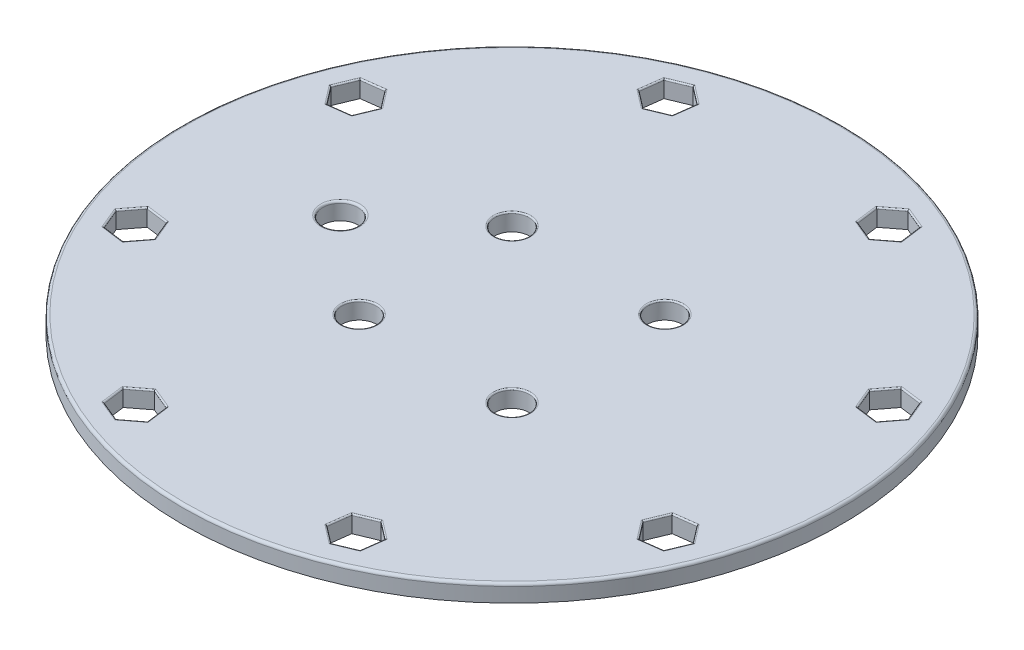
SolidWorks part; units mm, degrees
ref_plane "前视基准面" through (0, 0, 0) normal (0, 0, 1) x (1, 0, 0)
ref_plane "上视基准面" through (0, 0, 0) normal (0, 1, 0) x (1, 0, 0)
ref_plane "右视基准面" through (0, 0, 0) normal (1, 0, 0) x (0, 0, -1)
other "Configuration Table"
sketch "草图1" plane through (0, 0, 0) normal (0, 0, 1) x (1, 0, 0)
  line L0 (48, 6) -> (0, 6)
  line L1 (0, 6) -> (0, 0)
  line L2 (0, 0) -> (48, 0)
  line L3 (48, 0) -> (48, 6)
  line L4 (0, 6) -> (0, 0) construction
revolve "旋转1" add sketch "草图1" angle 360 about L4
sketch "草图2" plane through (0, 6, 0) normal (0, 1, 0) x (-1, 0, 0)
  line L0 (42.0084, 15.6507) -> (40.7712, 18.6377)
  line L1 (40.7712, 18.6377) -> (37.5657, 19.0598)
  line L2 (37.5657, 19.0598) -> (35.5974, 16.4947)
  line L3 (35.5974, 16.4947) -> (36.8347, 13.5077)
  line L4 (36.8347, 13.5077) -> (40.0402, 13.0857)
  line L5 (40.0402, 13.0857) -> (42.0084, 15.6507)
extrude "切除-拉伸1" cut sketch "草图2" against normal blind 2.5
sketch "草图3" plane through (0, 6, 0) normal (0, 1, 0) x (-1, 0, 0)
  line L0 (18.6377, 40.7712) -> (15.6507, 42.0084)
  line L1 (15.6507, 42.0084) -> (13.0857, 40.0402)
  line L2 (13.0857, 40.0402) -> (13.5077, 36.8347)
  line L3 (13.5077, 36.8347) -> (16.4947, 35.5974)
  line L4 (16.4947, 35.5974) -> (19.0598, 37.5657)
  line L5 (19.0598, 37.5657) -> (18.6377, 40.7712)
extrude "切除-拉伸2" cut sketch "草图3" against normal blind 2.5
sketch "草图4" plane through (0, 6, 0) normal (0, 1, 0) x (-1, 0, 0)
  line L0 (-15.6507, 42.0084) -> (-18.6377, 40.7712)
  line L1 (-18.6377, 40.7712) -> (-19.0598, 37.5657)
  line L2 (-19.0598, 37.5657) -> (-16.4947, 35.5974)
  line L3 (-16.4947, 35.5974) -> (-13.5077, 36.8347)
  line L4 (-13.5077, 36.8347) -> (-13.0857, 40.0402)
  line L5 (-13.0857, 40.0402) -> (-15.6507, 42.0084)
extrude "切除-拉伸3" cut sketch "草图4" against normal blind 2.5
sketch "草图5" plane through (0, 6, 0) normal (0, 1, 0) x (-1, 0, 0)
  line L0 (-40.7712, 18.6377) -> (-42.0084, 15.6507)
  line L1 (-42.0084, 15.6507) -> (-40.0402, 13.0857)
  line L2 (-40.0402, 13.0857) -> (-36.8347, 13.5077)
  line L3 (-36.8347, 13.5077) -> (-35.5974, 16.4947)
  line L4 (-35.5974, 16.4947) -> (-37.5657, 19.0598)
  line L5 (-37.5657, 19.0598) -> (-40.7712, 18.6377)
extrude "切除-拉伸4" cut sketch "草图5" against normal blind 2.5
sketch "草图6" plane through (0, 6, 0) normal (0, 1, 0) x (-1, 0, 0)
  line L0 (-42.0084, -15.6507) -> (-40.7712, -18.6377)
  line L1 (-40.7712, -18.6377) -> (-37.5657, -19.0598)
  line L2 (-37.5657, -19.0598) -> (-35.5974, -16.4947)
  line L3 (-35.5974, -16.4947) -> (-36.8347, -13.5077)
  line L4 (-36.8347, -13.5077) -> (-40.0402, -13.0857)
  line L5 (-40.0402, -13.0857) -> (-42.0084, -15.6507)
extrude "切除-拉伸5" cut sketch "草图6" against normal blind 2.5
sketch "草图7" plane through (0, 6, 0) normal (0, 1, 0) x (-1, 0, 0)
  line L0 (-18.6377, -40.7712) -> (-15.6507, -42.0084)
  line L1 (-15.6507, -42.0084) -> (-13.0857, -40.0402)
  line L2 (-13.0857, -40.0402) -> (-13.5077, -36.8347)
  line L3 (-13.5077, -36.8347) -> (-16.4947, -35.5974)
  line L4 (-16.4947, -35.5974) -> (-19.0598, -37.5657)
  line L5 (-19.0598, -37.5657) -> (-18.6377, -40.7712)
extrude "切除-拉伸6" cut sketch "草图7" against normal blind 2.5
sketch "草图8" plane through (0, 6, 0) normal (0, 1, 0) x (-1, 0, 0)
  line L0 (15.6507, -42.0084) -> (18.6377, -40.7712)
  line L1 (18.6377, -40.7712) -> (19.0598, -37.5657)
  line L2 (19.0598, -37.5657) -> (16.4947, -35.5974)
  line L3 (16.4947, -35.5974) -> (13.5077, -36.8347)
  line L4 (13.5077, -36.8347) -> (13.0857, -40.0402)
  line L5 (13.0857, -40.0402) -> (15.6507, -42.0084)
extrude "切除-拉伸7" cut sketch "草图8" against normal blind 2.5
sketch "草图9" plane through (0, 6, 0) normal (0, 1, 0) x (-1, 0, 0)
  line L0 (40.7712, -18.6377) -> (42.0084, -15.6507)
  line L1 (42.0084, -15.6507) -> (40.0402, -13.0857)
  line L2 (40.0402, -13.0857) -> (36.8347, -13.5077)
  line L3 (36.8347, -13.5077) -> (35.5974, -16.4947)
  line L4 (35.5974, -16.4947) -> (37.5657, -19.0598)
  line L5 (37.5657, -19.0598) -> (40.7712, -18.6377)
extrude "切除-拉伸8" cut sketch "草图9" against normal blind 2.5
hole_wizard "Ø5.0 (5) 直径孔1" positions "草图11" profile "草图10" hole size "Ø5.0" standard "ANSI Metric"
sketch "草图11" plane through (0, 6, 0) normal (0, 1, 0) x (1, 0, 0)
  point P0 (11.1369, 11.1369)
  point P1 (11.1369, -11.1369)
  point P2 (-11.1369, -11.1369)
  point P3 (-11.1369, 11.1369)
sketch "草图10" plane through (11.1369, 6, -11.1369) normal (1, 0, 0) x (0, 0, 1)
  line L0 (0, 0) -> (0, 6)
  line L1 (0, 6) -> (2.5, 6)
  line L2 (2.5, 6) -> (2.5, 0)
  line L5 (2.5, 0) -> (0, 0)
  line L11 (0, -6.35) -> (0, 107.95) construction
  dimension "通孔孔直径" = 5
  dimension "通孔孔深度" = 6
hole_wizard "Ø3.0 (3) 直径孔1" positions "草图13" profile "草图12" hole size "Ø3.0" standard "ANSI Metric"
sketch "草图13" plane through (0, 3.5, 0) normal (0, 1, 0) x (1, 0, 0)
  point P0 (-38.8029, -16.0727)
  point P1 (-16.0727, -38.8029)
  point P2 (16.0727, -38.8029)
  point P3 (38.8029, -16.0727)
  point P4 (38.8029, 16.0727)
  point P5 (16.0727, 38.8029)
  point P6 (-16.0727, 38.8029)
  point P7 (-38.8029, 16.0727)
sketch "草图12" plane through (-38.8029, 3.5, 16.0727) normal (1, 0, 0) x (0, 0, 1)
  line L0 (0, 0) -> (0, 3.5)
  line L1 (0, 3.5) -> (1.5, 3.5)
  line L2 (1.5, 3.5) -> (1.5, 0)
  line L5 (1.5, 0) -> (0, 0)
  line L11 (0, -6.35) -> (0, 107.95) construction
  dimension "通孔孔直径" = 3
  dimension "通孔孔深度" = 3.5
hole_wizard "Ø5.1 (5.1) 直径孔1" positions "草图15" profile "草图14" hole size "Ø5.1" standard "ANSI Metric"
sketch "草图15" plane through (0, 6, 0) normal (0, 1, 0) x (1, 0, 0)
  point P0 (-25, 0)
sketch "草图14" plane through (-25, 6, 0) normal (1, 0, 0) x (0, 0, 1)
  line L0 (0, 0) -> (0, 3.5)
  line L1 (0, 3.5) -> (2.55, 3.5)
  line L2 (2.55, 3.5) -> (2.55, 0)
  line L5 (2.55, 0) -> (0, 0)
  line L10 (0, 3.5) -> (-2.55, 3.5) construction
  line L11 (0, -6.35) -> (0, 107.95) construction
  dimension "孔直径" = 5.1
  dimension "孔深度" = 3.5
  dimension "导头角度" = 180
fillet "圆角1" radius 0.2 60 edges at (-41.3898, 6, -17.1442) (-41.0243, 6, -14.3682) (-39.1684, 6, -18.8487) (-38.4375, 6, -13.2967) (-36.5816, 6, -17.7772) (-36.2161, 6, -15.0012) (18.8487, 6, -39.1684) (17.1442, 6, -41.3898) (17.7772, 6, -36.5816) (14.3682, 6, -41.0243) (15.0012, 6, -36.2161) (13.2967, 6, -38.4375) (-36.5816, 6, 17.7772) (-39.1684, 6, 18.8487) (-36.2161, 6, 15.0012) (-41.3898, 6, 17.1442) (-38.4375, 6, 13.2967) (-41.0243, 6, 14.3682) (-16.0727, 3.5, -37.3029) (-17.1442, 6, -41.3898) (-18.8487, 6, -39.1684) (-14.3682, 6, -41.0243) (-17.7772, 6, -36.5816) (-13.2967, 6, -38.4375) (-15.0012, 6, -36.2161) (-38.8029, 3.5, 17.5727) (41.3898, 6, -17.1442) (39.1684, 6, -18.8487) (41.0243, 6, -14.3682) (36.5816, 6, -17.7772) (38.4375, 6, -13.2967) (36.2161, 6, -15.0012) (-13.2967, 6, 38.4375) (-14.3682, 6, 41.0243) (-15.0012, 6, 36.2161) (-17.1442, 6, 41.3898) (-17.7772, 6, 36.5816) (-18.8487, 6, 39.1684) (16.0727, 3.5, 40.3029) (17.7772, 6, 36.5816) (18.8487, 6, 39.1684) (15.0012, 6, 36.2161) (17.1442, 6, 41.3898) (13.2967, 6, 38.4375) (14.3682, 6, 41.0243) (38.4375, 6, 13.2967) (41.0243, 6, 14.3682) (36.2161, 6, 15.0012) (41.3898, 6, 17.1442) (36.5816, 6, 17.7772) (39.1684, 6, 18.8487) (-16.0727, 3.5, 40.3029) (16.0727, 3.5, -37.3029) (-11.1369, 6, 13.6369) (11.1369, 6, -8.6369) (-38.8029, 3.5, -14.5727) (11.1369, 6, 13.6369) (38.8029, 3.5, 17.5727) (-11.1369, 6, -8.6369) (38.8029, 3.5, -14.5727)
fillet "圆角2" radius 0.3 1 edges at (-25, 6, 2.55)
fillet "圆角3" radius 0.4 1 edges at (0, 6, -48)
sketch "草图16" plane through (0, 0, 0) normal (0, -1, 0) x (1, 0, 0)
  circle A0 centre (0, 0) radius 48
extrude "切除-拉伸9" cut sketch "草图16" against normal blind 3.5
